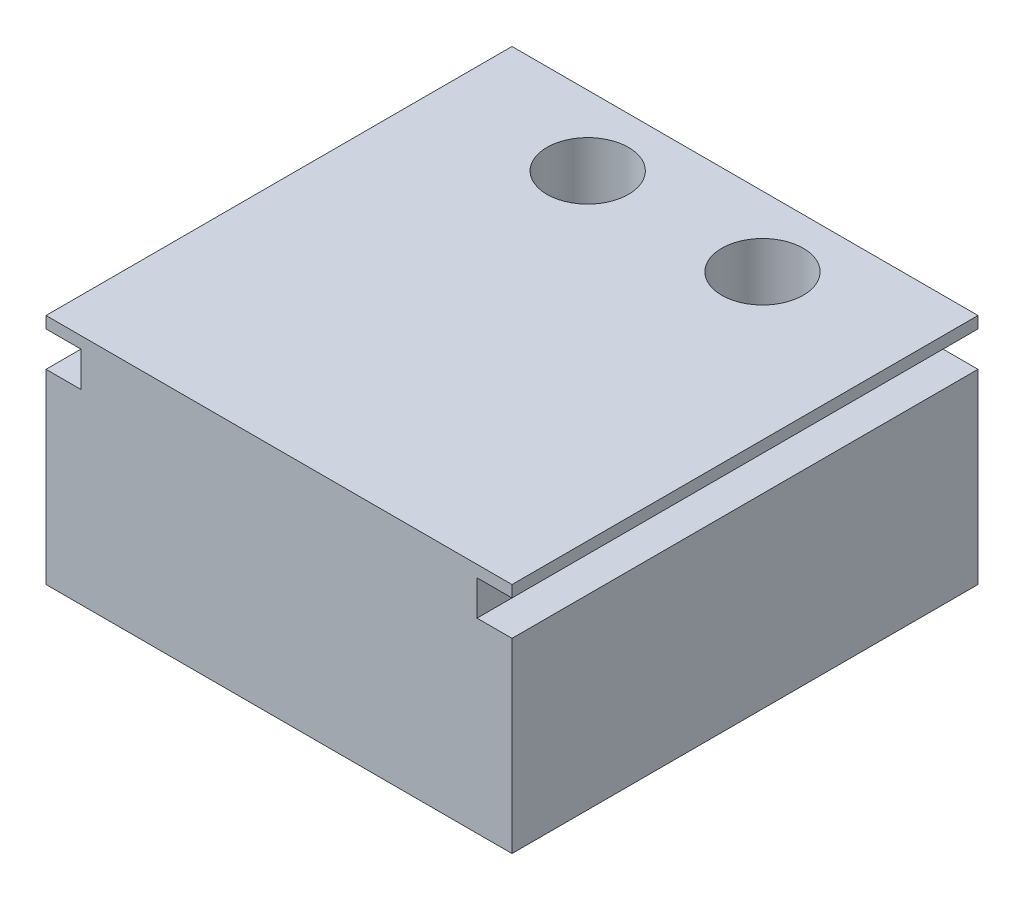
SolidWorks part; units mm, degrees
ref_plane "Front Plane" through (0, 0, 0) normal (0, 0, 1) x (1, 0, 0)
ref_plane "Top Plane" through (0, 0, 0) normal (0, 1, 0) x (1, 0, 0)
ref_plane "Right Plane" through (0, 0, 0) normal (1, 0, 0) x (0, 0, -1)
sketch "Sketch1" plane through (0, 0, 0) normal (0, 1, 0) x (1, 0, 0)
  line L0 (14.146, -8.4912) -> (-25.854, -8.4912)
  line L1 (-25.854, -8.4912) -> (-25.854, 31.5088)
  line L2 (-25.854, 31.5088) -> (14.146, 31.5088)
  line L3 (14.146, 31.5088) -> (14.146, -8.4912)
  dimension "D1" = 40
  dimension "D2" = 40
extrude "Boss-Extrude1" add sketch "Sketch1" along normal blind 20
sketch "Sketch2" plane through (0, 20, 0) normal (0, 1, 0) x (1, 0, 0)
  line L0 (14.146, -8.4912) -> (14.146, 31.5088) construction
  line L1 (-25.854, 31.5088) -> (-25.854, -8.4912) construction
  line L2 (14.146, 31.5088) -> (-25.854, 31.5088) construction
  line L3 (-13.354, 25.5088) -> (22.2805, 25.5088) construction
  circle A0 centre (-13.354, 25.5088) radius 3.5
  circle A1 centre (1.646, 25.5088) radius 3.5
  dimension "D1" = 7
  dimension "D2" = 7
  dimension "D3" = 12.5
  dimension "D4" = 12.5
  dimension "D5" = 6
extrude "Cut-Extrude1" cut sketch "Sketch2" against normal blind 15
sketch "Sketch3" plane through (14.146, 0, 0) normal (1, 0, 0) x (0, 0, -1)
  line L0 (-8.4912, 20) -> (-8.4912, 0) construction
  line L1 (-8.4912, 19) -> (31.5088, 19)
  line L2 (-8.4912, 19) -> (-8.4912, 16)
  line L3 (-8.4912, 16) -> (31.5088, 16)
  line L4 (31.5088, 19) -> (31.5088, 16)
  line L5 (31.5088, 20) -> (31.5088, 0) construction
  dimension "D1" = 3
  dimension "D2" = 1
extrude "Cut-Extrude2" cut sketch "Sketch3" against normal blind 3
ref_plane "Plane1" through (-5.854, 0, 0) normal (1, 0, 0) x (0, 0, -1)
mirror "Mirror1" about plane through (-5.854, 0, 0) normal (1, 0, 0) of "Cut-Extrude2"
